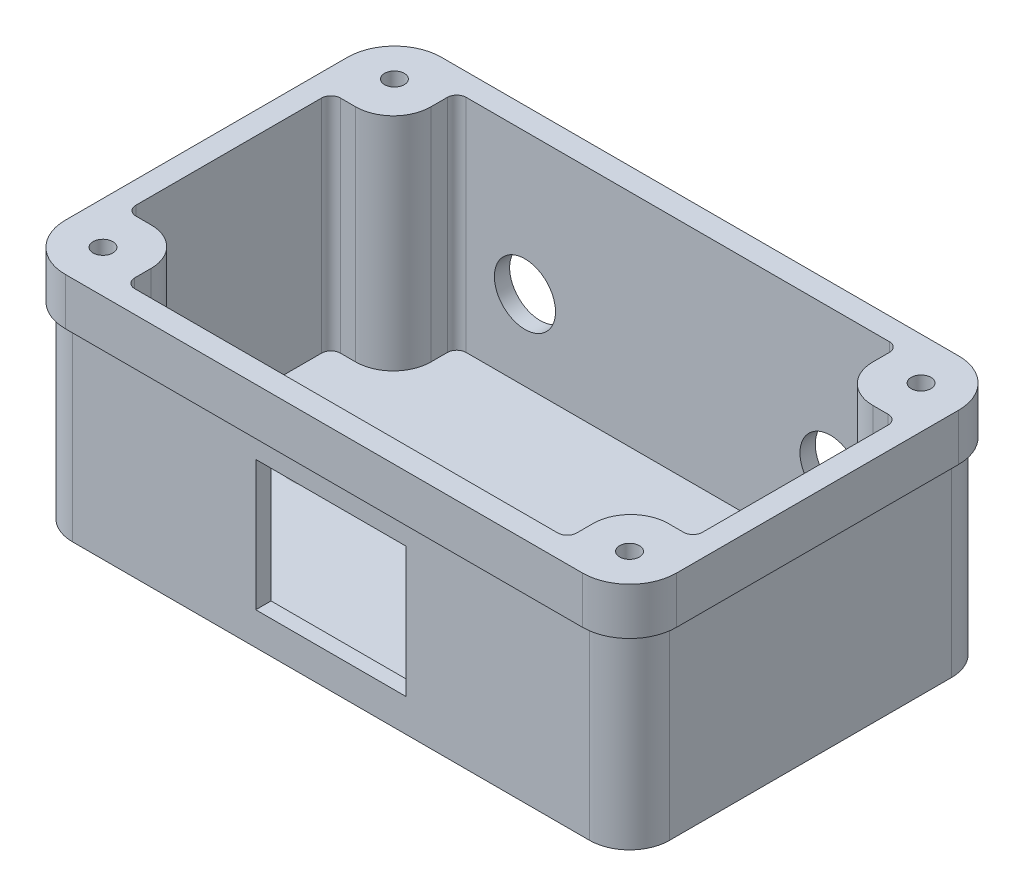
SolidWorks part; units mm, degrees
ref_plane "Front Plane" through (0, 0, 0) normal (0, 0, 1) x (1, 0, 0)
ref_plane "Top Plane" through (0, 0, 0) normal (0, 1, 0) x (1, 0, 0)
ref_plane "Right Plane" through (0, 0, 0) normal (1, 0, 0) x (0, 0, -1)
sketch "Sketch1" plane through (0, 0, 0) normal (0, 1, 0) x (1, 0, 0)
  line L1 (-55, 40) -> (55, 40)
  line L2 (-65, 30) -> (-65, -30)
  line L3 (-55, -40) -> (55, -40)
  line L4 (65, 30) -> (65, -30)
  line L5 (-65, 40) -> (65, -40) construction
  line L6 (-65, -40) -> (65, 40) construction
  arc A0 (-65, -30) -> (-55, -40) centre (-55, -30) ccw
  arc A1 (55, -40) -> (65, -30) centre (55, -30) ccw
  arc A2 (55, 40) -> (65, 30) centre (55, 30) cw
  arc A3 (-55, 40) -> (-65, 30) centre (-55, 30) ccw
  point P0 (0, 0)
  dimension "D3" = 10
  dimension "D1" = 130
  dimension "D2" = 80
extrude "Boss-Extrude1" add sketch "Sketch1" along normal blind 50
shell "Shell1" thickness 3
sketch "Sketch2" plane through (0, 0, 0) normal (0, -1, 0) x (1, 0, 0)
  line L0 (-63.5, 30) -> (-63.5, -30)
  line L1 (-55, -38.5) -> (55, -38.5)
  line L2 (63.5, -30) -> (63.5, 30)
  line L3 (55, 38.5) -> (-55, 38.5)
  line L8 (65, -30) -> (65, 30)
  line L9 (55, 40) -> (-55, 40)
  line L10 (-65, 30) -> (-65, -30)
  line L11 (-55, -40) -> (55, -40)
  line L12 (65, -30) -> (65, 30)
  line L13 (55, 40) -> (-55, 40)
  line L14 (-65, 30) -> (-65, -30)
  line L15 (-55, -40) -> (55, -40)
  arc A0 (-55, 38.5) -> (-63.5, 30) centre (-55, 30) ccw
  arc A1 (-63.5, -30) -> (-55, -38.5) centre (-55, -30) ccw
  arc A2 (55, -38.5) -> (63.5, -30) centre (55, -30) ccw
  arc A3 (63.5, 30) -> (55, 38.5) centre (55, 30) ccw
  arc A4 (-55, 40) -> (-65, 30) centre (-55, 30) ccw
  arc A5 (-55, 40) -> (-65, 30) centre (-55, 30) ccw
  arc A6 (-65, -30) -> (-55, -40) centre (-55, -30) ccw
  arc A7 (-65, -30) -> (-55, -40) centre (-55, -30) ccw
  arc A8 (55, -40) -> (65, -30) centre (55, -30) ccw
  arc A9 (55, -40) -> (65, -30) centre (55, -30) ccw
  arc A10 (65, 30) -> (55, 40) centre (55, 30) ccw
  arc A11 (65, 30) -> (55, 40) centre (55, 30) ccw
  dimension "D1" = 0
  dimension "D2" = 1.5
extrude "Cut-Extrude1" cut sketch "Sketch2" against normal blind 40
sketch "Sketch3" plane through (0, 3, 0) normal (0, 1, 0) x (1, 0, 0)
  line L4 (0, 40) -> (0, -40) construction
  line L9 (55, 40) -> (-55, 40) construction
  line L16 (-55, -40) -> (55, -40) construction
  line L17 (-65, 0) -> (65, 0) construction
  line L18 (-65, 30) -> (-65, -30) construction
  line L19 (65, -30) -> (65, 30) construction
  line L20 (-58.25, 21.75) -> (-55, 21.75)
  line L21 (-45, 35.25) -> (45, 35.25)
  line L22 (-60.25, 19.75) -> (-60.25, -19.75)
  line L23 (-45, -35.25) -> (45, -35.25)
  line L24 (60.25, 19.75) -> (60.25, -19.75)
  line L25 (-60.25, 35.25) -> (60.25, -35.25) construction
  line L26 (-60.25, -35.25) -> (60.25, 35.25) construction
  line L27 (-47, 29.75) -> (-47, 33.25)
  line L28 (47, 29.75) -> (47, 33.25)
  line L29 (58.25, 21.75) -> (55, 21.75)
  line L30 (47, -29.75) -> (47, -33.25)
  line L31 (58.25, -21.75) -> (55, -21.75)
  line L32 (-58.25, -21.75) -> (-55, -21.75)
  line L33 (-47, -29.75) -> (-47, -33.25)
  line L34 (62, -30) -> (62, 30) construction
  line L35 (-55, -37) -> (55, -37) construction
  line L36 (-62, 30) -> (-62, -30) construction
  line L37 (55, 37) -> (-55, 37) construction
  line L38 (62, -30) -> (62, 30)
  line L39 (-55, -37) -> (55, -37)
  line L40 (-62, 30) -> (-62, -30)
  line L41 (55, 37) -> (-55, 37)
  circle A8 centre (-56, 31) radius 2.1
  circle A9 centre (56, 31) radius 2.1
  circle A10 centre (56, -31) radius 2.1
  circle A11 centre (-56, -31) radius 2.1
  arc A12 (-55, -21.75) -> (-47, -29.75) centre (-55, -29.75) cw
  arc A13 (47, -29.75) -> (55, -21.75) centre (55, -29.75) cw
  arc A14 (47, 29.75) -> (55, 21.75) centre (55, 29.75) ccw
  arc A15 (-55, 21.75) -> (-47, 29.75) centre (-55, 29.75) ccw
  arc A16 (-47, -33.25) -> (-45, -35.25) centre (-45, -33.25) ccw
  arc A17 (-60.25, -19.75) -> (-58.25, -21.75) centre (-58.25, -19.75) ccw
  arc A18 (45, -35.25) -> (47, -33.25) centre (45, -33.25) ccw
  arc A19 (58.25, -21.75) -> (60.25, -19.75) centre (58.25, -19.75) ccw
  arc A20 (60.25, 19.75) -> (58.25, 21.75) centre (58.25, 19.75) ccw
  arc A21 (45, 35.25) -> (47, 33.25) centre (45, 33.25) cw
  arc A22 (-60.25, 19.75) -> (-58.25, 21.75) centre (-58.25, 19.75) cw
  arc A23 (-45, 35.25) -> (-47, 33.25) centre (-45, 33.25) ccw
  arc A24 (62, 30) -> (55, 37) centre (55, 30) ccw construction
  arc A25 (55, -37) -> (62, -30) centre (55, -30) ccw construction
  arc A26 (-62, -30) -> (-55, -37) centre (-55, -30) ccw construction
  arc A27 (-55, 37) -> (-62, 30) centre (-55, 30) ccw construction
  arc A28 (62, 30) -> (55, 37) centre (55, 30) ccw
  arc A29 (55, -37) -> (62, -30) centre (55, -30) ccw
  arc A30 (-62, -30) -> (-55, -37) centre (-55, -30) ccw
  arc A31 (-55, 37) -> (-62, 30) centre (-55, 30) ccw
  point P22 (0, 0)
  point P41 (-47, -21.75)
  point P44 (47, -21.75)
  point P47 (47, 21.75)
  point P50 (-47, 21.75)
  dimension "D1" = 4.2
  dimension "D8" = 8
  dimension "D5" = 2
  dimension "D2" = 112
  dimension "D3" = 62
  dimension "D4" = 120.5
  dimension "D6" = 43.5
  dimension "D7" = 94
extrude "Boss-Extrude5" add sketch "Sketch3" along normal blind 47 separate body
sketch "Sketch5" plane through (0, 3, 0) normal (0, 1, 0) x (1, 0, 0)
  line L0 (-65, 0) -> (65, 0) construction
  line L1 (-65, 30) -> (-65, -30) construction
  line L2 (65, -30) -> (65, 30) construction
  line L3 (0, 40) -> (0, -40) construction
  line L4 (55, 40) -> (-55, 40) construction
  line L5 (-55, -40) -> (55, -40) construction
  circle A0 centre (-40, 0) radius 2
  circle A1 centre (40, 0) radius 2
  dimension "D1" = 4
  dimension "D2" = 80
extrude "Cut-Extrude2" cut sketch "Sketch5" against normal blind 10
sketch "Sketch6" plane through (0, 3, 0) normal (0, 1, 0) x (1, 0, 0)
  line L4 (0, 40) -> (0, -40) construction
  line L5 (55, 40) -> (-55, 40) construction
  line L6 (-55, -40) -> (55, -40) construction
  circle A4 centre (-40, 0) radius 2 construction
  circle A8 centre (-40, 0) radius 2
  circle A9 centre (-40, 0) radius 6
  circle A10 centre (40, 0) radius 2
  circle A11 centre (40, 0) radius 6
  dimension "D1" = 12
extrude "Boss-Extrude6" add sketch "Sketch6" along normal blind 3
fillet "Fillet1" radius 1 4 edges at (40, 6, -6) (40, 3, -6) (-40, 6, 6) (-40, 3, 6)
sketch "Sketch7" plane through (0, 0, 38.5) normal (0, 0, 1) x (1, 0, 0)
  line L0 (0, 0) -> (0, 50) construction
  line L1 (55, 0) -> (-55, 0) construction
  line L2 (-55, 50) -> (55, 50) construction
  line L4 (-16, 34.6803) -> (16, 34.6803)
  line L5 (-16, 34.6803) -> (-16, 6.9803)
  line L6 (-16, 6.9803) -> (16, 6.9803)
  line L7 (16, 34.6803) -> (16, 6.9803)
  line L8 (-16, 34.6803) -> (16, 6.9803) construction
  line L9 (-16, 6.9803) -> (16, 34.6803) construction
  point P6 (0, 20.8303)
  dimension "D1" = 32
  dimension "D2" = 27.7
extrude "Cut-Extrude3" cut sketch "Sketch7" against normal blind 10
sketch "Sketch8" plane through (0, 0, -38.5) normal (0, 0, -1) x (-1, 0, 0)
  line L0 (0, 40) -> (0, 0) construction
  line L1 (55, 40) -> (-55, 40) construction
  circle A0 centre (-32.5, 20) radius 6.5
  circle A1 centre (32.5, 20) radius 6.5
  dimension "D2" = 13
  dimension "D1" = 65
extrude "Cut-Extrude4" cut sketch "Sketch8" against normal blind 10
